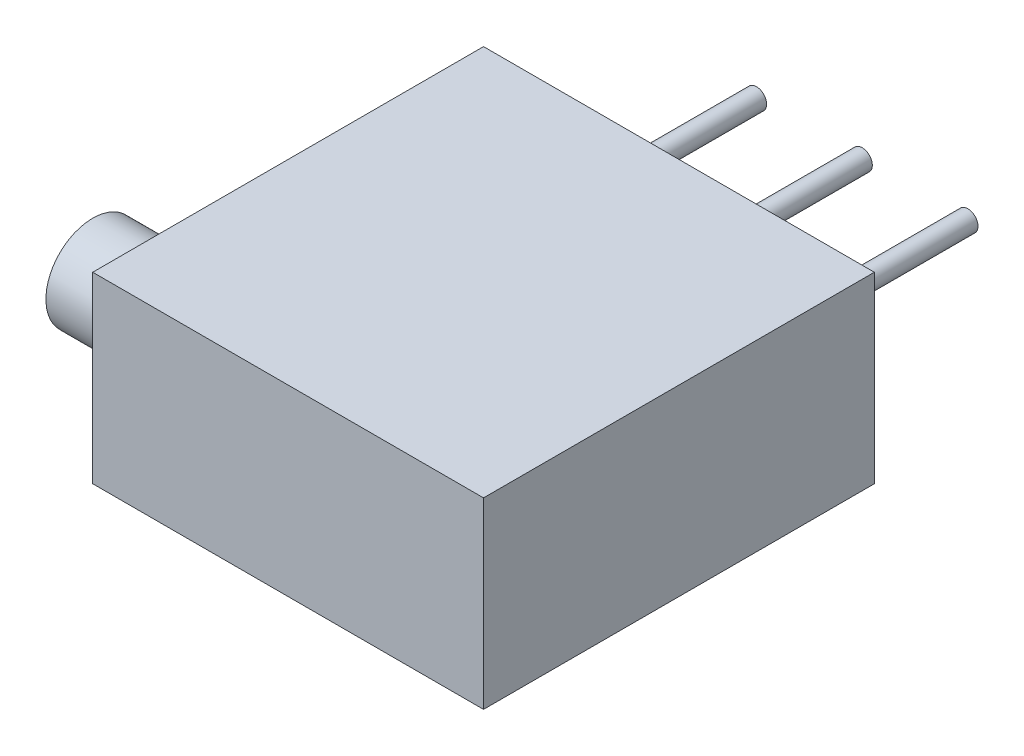
SolidWorks part; units mm, degrees
ref_plane "前视" through (0, 0, 0) normal (0, 0, 1) x (1, 0, 0)
ref_plane "上视" through (0, 0, 0) normal (0, 1, 0) x (1, 0, 0)
ref_plane "右视" through (0, 0, 0) normal (1, 0, 0) x (0, 0, -1)
sketch "草图1" plane through (0, 0, 0) normal (0, 1, 0) x (1, 0, 0)
  line L0 (0, 81.3418) -> (0, -101.3275) construction
  line L1 (-87.3375, 0) -> (113.7186, 0) construction
  line L3 (-4.8, 4.8) -> (4.8, 4.8)
  line L4 (-4.8, 4.8) -> (-4.8, -4.8)
  line L5 (-4.8, -4.8) -> (4.8, -4.8)
  line L6 (4.8, 4.8) -> (4.8, -4.8)
  dimension "D1" = 9.6
  dimension "D2" = 9.6
extrude "拉伸1" add sketch "草图1" along normal blind 4.5
sketch "草图3" plane through (0, 0, -4.8) normal (0, 0, -1) x (-1, 0, 0)
  line L0 (-5.1663, 2.25) -> (6.6013, 2.25) construction
  line L2 (0, 5.9307) -> (0, -2.165) construction
  circle A0 centre (0, 2.25) radius 0.25
  circle A1 centre (2.596, 2.25) radius 0.25
  circle A2 centre (-2.596, 2.25) radius 0.25
  dimension "D1" = 0.5
extrude "拉伸3" add sketch "草图3" along normal blind 4.5
sketch "草图4" plane through (-4.8, 0, 0) normal (1, 0, 0) x (0, 0, -1)
  line L0 (-4.8, 4.5) -> (-4.8, 0) construction
  line L2 (-4.8, 4.5) -> (4.8, 4.5) construction
  circle A0 centre (-3.3, 3) radius 1.15
  dimension "D1" = 2.3
  dimension "D2" = 1.5
  dimension "D3" = 1.5
extrude "拉伸4" add sketch "草图4" against normal blind 1.5
